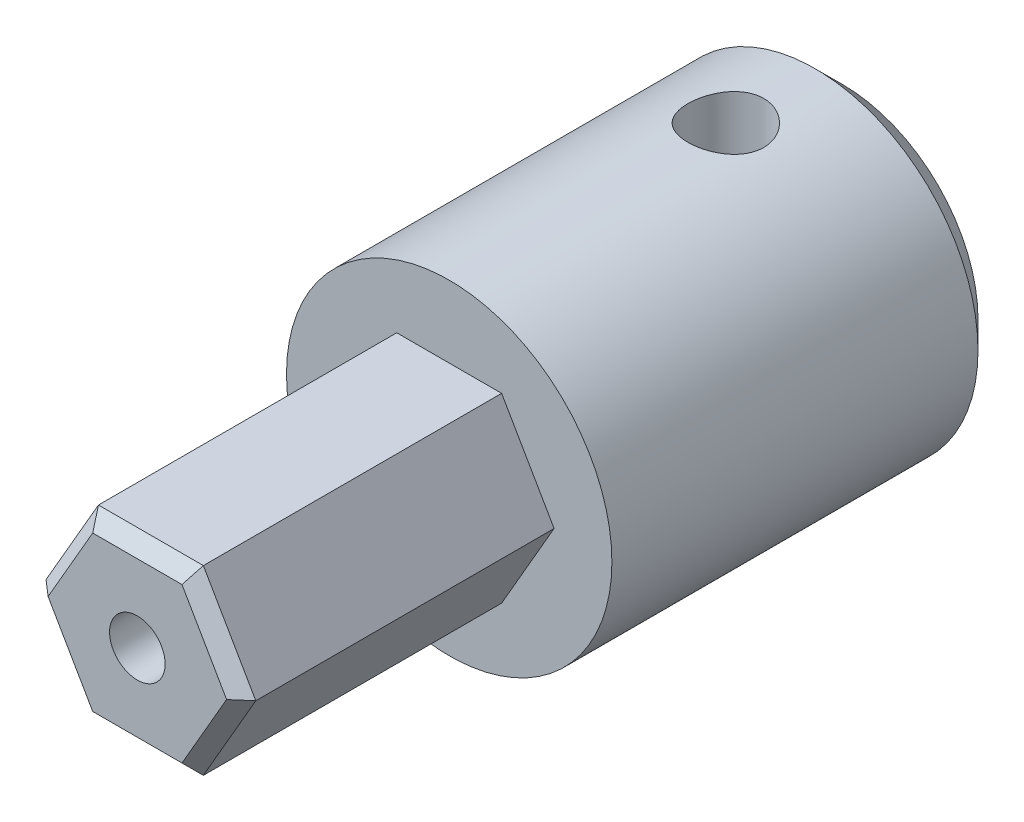
SolidWorks part; units mm, degrees
ref_plane "前视基准面" through (0, 0, 0) normal (0, 0, 1) x (1, 0, 0)
ref_plane "上视基准面" through (0, 0, 0) normal (0, 1, 0) x (1, 0, 0)
ref_plane "右视基准面" through (0, 0, 0) normal (1, 0, 0) x (0, 0, -1)
sketch "草图1" plane through (0, 0, 0) normal (0, 0, 1) x (1, 0, 0)
  circle A0 centre (0, 0) radius 6
  dimension "D1" = 12
extrude "凸台-拉伸1" add sketch "草图1" along normal blind 14.5
sketch "草图2" plane through (0, 0, 14.5) normal (0, 0, 1) x (1, 0, 0)
  line L1 (3.8682, 0) -> (1.9341, 3.35)
  line L2 (1.9341, 3.35) -> (-1.9341, 3.35)
  line L3 (-1.9341, 3.35) -> (-3.8682, 0)
  line L4 (-3.8682, 0) -> (-1.9341, -3.35)
  line L5 (-1.9341, -3.35) -> (1.9341, -3.35)
  line L6 (1.9341, -3.35) -> (3.8682, 0)
  circle A0 centre (0, 0) radius 3.35 construction
  dimension "D1" = 6.7
extrude "凸台-拉伸2" add sketch "草图2" along normal blind 11.5
sketch "草图4" plane through (0, 0, 26) normal (0, 0, 1) x (1, 0, 0)
  point P0 (0, 0)
hole_wizard "M2.5 螺纹孔1" positions "3D草图2" profile "草图5" tap size "M2.5" standard "GB"
sketch3d "3D草图2"
  point P0 (0, 0, 26)
sketch "草图5" plane through (0, 0, 26) normal (1, 0, 0) x (0, -1, 0)
  line L0 (0, 0) -> (0, 11.6159)
  line L1 (0, 11.6159) -> (1.025, 11)
  line L2 (1.025, 11) -> (1.025, 0)
  line L5 (1.025, 0) -> (0, 0)
  line L10 (0, 11.6159) -> (-1.025, 11) construction
  line L11 (0, -6.35) -> (0, 107.95) construction
  dimension "螺纹孔钻头直径" = 2.05
  dimension "螺纹孔钻头深度" = 11
  dimension "导头角度" = 118
cosmetic thread "孔螺蚊线1" parameters "D1"=10, "D2"=2.5
sketch "草图6" plane through (0, 0, 0) normal (0, 0, -1) x (-1, 0, 0)
  circle A0 centre (0, 0) radius 3
  dimension "D1" = 6
extrude "切除-拉伸1" cut sketch "草图6" against normal blind 12
chamfer "倒角2" distance 1 angle 45 1 edges at (6, 0, 0)
chamfer "倒角3" distance 0.5 distance2 0.5 6 edges at (0, 3.35, 26) (-2.9012, 1.675, 26) (-2.9012, -1.675, 26) (0, -3.35, 26) (2.9012, -1.675, 26) (2.9012, 1.675, 26)
ref_plane "基准面1" through (0, 6, 0) normal (0, 1, 0) x (1, 0, 0)
sketch "草图7" plane through (0, 6, 0) normal (0, 1, 0) x (1, 0, 0)
  line L0 (5, 0) -> (-5, 0) construction
  circle A0 centre (0, -4.3) radius 1.4
  point P4 (0, 0)
  dimension "D1" = 2.8
  dimension "D2" = 4.3
extrude "切除-拉伸2" cut sketch "草图7" against normal blind 6
sketch "草图9" plane through (0, 6, 0) normal (0, 1, 0) x (1, 0, 0)
  point P0 (0, -4.3)
